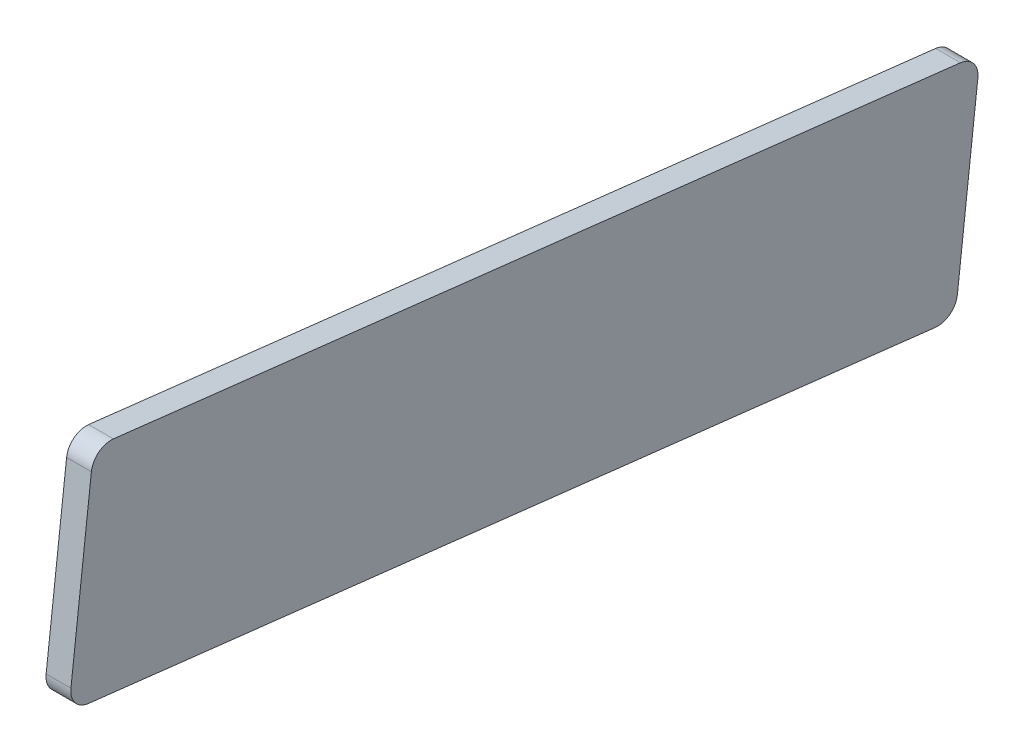
SolidWorks part; units mm, degrees
material "Acrylic (Medium-high impact)"
ref_plane "Front Plane" through (0, 0, 0) normal (0, 0, 1) x (1, 0, 0)
ref_plane "Top Plane" through (0, 0, 0) normal (0, 1, 0) x (1, 0, 0)
ref_plane "Right Plane" through (0, 0, 0) normal (1, 0, 0) x (0, 0, -1)
sketch "Sketch1" plane through (-230.5, 0, 0) normal (-1, 0, 0) x (0, 0, 1)
  line L4 (-346.7151, 353.8417) -> (-344.6512, 335.9604)
  line L5 (-342.4351, 334.2029) -> (-257.0023, 344.0637)
  line L6 (-255.2448, 346.2798) -> (-257.3087, 364.1611)
  line L7 (-259.5248, 365.9186) -> (-344.9576, 356.0578)
  line L8 (-346.7151, 353.8417) -> (-344.6512, 335.9604)
  line L9 (-342.4351, 334.2029) -> (-257.0023, 344.0637)
  line L10 (-255.2448, 346.2798) -> (-257.3087, 364.1611)
  line L11 (-259.5248, 365.9186) -> (-344.9576, 356.0578)
  arc A8 (-257.3087, 364.1611) -> (-259.5248, 365.9186) centre (-259.2955, 363.9318) ccw
  arc A9 (-257.3087, 364.1611) -> (-259.5248, 365.9186) centre (-259.2955, 363.9318) ccw
  arc A10 (-344.9576, 356.0578) -> (-346.7151, 353.8417) centre (-344.7283, 354.071) ccw
  arc A11 (-344.9576, 356.0578) -> (-346.7151, 353.8417) centre (-344.7283, 354.071) ccw
  arc A12 (-344.6512, 335.9604) -> (-342.4351, 334.2029) centre (-342.6644, 336.1897) ccw
  arc A13 (-344.6512, 335.9604) -> (-342.4351, 334.2029) centre (-342.6644, 336.1897) ccw
  arc A14 (-257.0023, 344.0637) -> (-255.2448, 346.2798) centre (-257.2316, 346.0505) ccw
  arc A15 (-257.0023, 344.0637) -> (-255.2448, 346.2798) centre (-257.2316, 346.0505) ccw
  dimension "D1" = 0
extrude "Boss-Extrude1" add sketch "Sketch1" along normal up to vertex (2.5 mm away)
